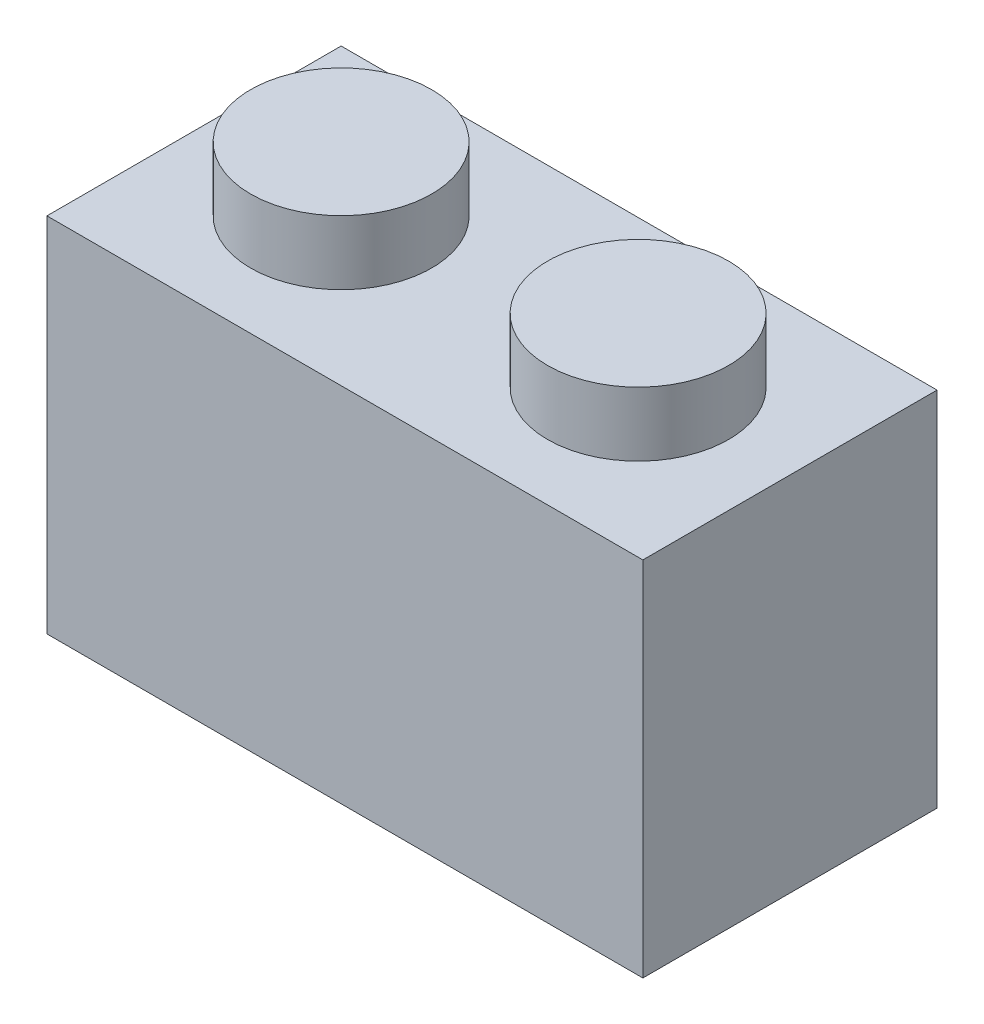
SolidWorks part; units mm, degrees
ref_plane "Спереди" through (0, 0, 0) normal (0, 0, 1) x (1, 0, 0)
ref_plane "Сверху" through (0, 0, 0) normal (0, 1, 0) x (1, 0, 0)
ref_plane "Справа" through (0, 0, 0) normal (1, 0, 0) x (0, 0, -1)
sketch "Эскиз1" plane through (0, 0, 0) normal (0, 1, 0) x (1, 0, 0)
  line L1 (7.9, -3.9) -> (-7.9, -3.9)
  line L2 (7.9, -3.9) -> (7.9, 3.9)
  line L3 (7.9, 3.9) -> (-7.9, 3.9)
  line L4 (-7.9, -3.9) -> (-7.9, 3.9)
  line L5 (7.9, -3.9) -> (-7.9, 3.9) construction
  line L6 (7.9, 3.9) -> (-7.9, -3.9) construction
  point P0 (0, 0)
  dimension "D1" = 15.8
  dimension "D2" = 7.8
extrude "Бобышка-Вытянуть2" add sketch "Эскиз1" along normal blind 9.6
sketch "Эскиз2" plane through (0, 9.6, 0) normal (0, 1, 0) x (1, 0, 0)
  line L0 (-7.9, 3.9) -> (-7.9, -3.9) construction
  line L1 (7.9, 3.9) -> (-7.9, 3.9) construction
  circle A0 centre (-4, 0) radius 2.4
  circle A1 centre (3.874, 0) radius 2.4
  dimension "D1" = 3.9
  dimension "D2" = 3.9
  dimension "D3" = 2
extrude "Бобышка-Вытянуть3" add sketch "Эскиз2" along normal blind 1.7
sketch "Эскиз3" plane through (0, 0, 0) normal (0, -1, 0) x (1, 0, 0)
  line L0 (-7.9, -3.9) -> (-7.9, 3.9) construction
  line L1 (7.9, -3.9) -> (-7.9, -3.9) construction
  circle A0 centre (-4, 0) radius 2.5
  circle A1 centre (3.874, 0) radius 2.5
  dimension "D1" = 3.9
  dimension "D2" = 3.9
  dimension "D3" = 2
extrude "Вырез-Вытянуть1" cut sketch "Эскиз3" against normal blind 1.8
